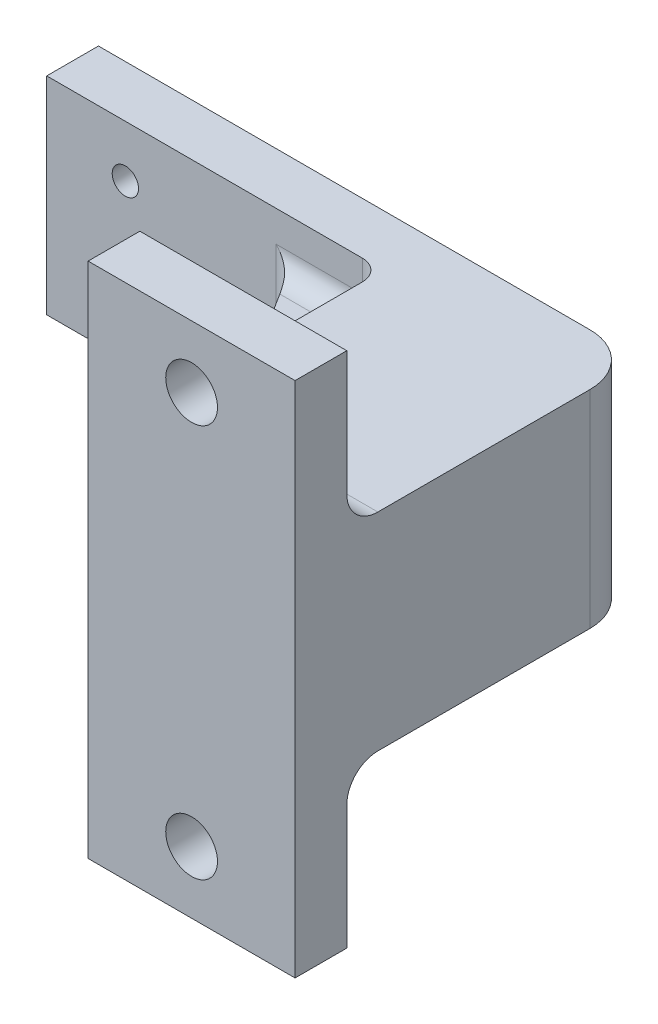
SolidWorks part; units mm, degrees
ref_plane "前视基准面" through (0, 0, 0) normal (0, 0, 1) x (1, 0, 0)
ref_plane "上视基准面" through (0, 0, 0) normal (0, 1, 0) x (1, 0, 0)
ref_plane "右视基准面" through (0, 0, 0) normal (1, 0, 0) x (0, 0, -1)
other "Configuration Table"
sketch "草图1" plane through (0, 0, 0) normal (0, 0, 1) x (1, 0, 0)
  line L1 (0, 0) -> (52.5, 0)
  line L2 (0, 0) -> (0, -20)
  line L3 (0, -20) -> (52.5, -20)
  line L4 (52.5, 0) -> (52.5, -20)
  circle A0 centre (7.6, -5) radius 1.27
  circle A1 centre (7.6, -15) radius 1.25
  point P9 (0, 0)
  dimension "D3" = 2.54
  dimension "D4" = 2.5
  dimension "D1" = 20
  dimension "D2" = 52.5
  dimension "D5" = 10
  dimension "D6" = 5
  dimension "D7" = 7.6
extrude "凸台-拉伸1" add sketch "草图1" along normal blind 5
sketch "草图2" plane through (0, 0, 5) normal (0, 0, 1) x (1, 0, 0)
  line L0 (0, -20) -> (52.5, -20) construction
  line L1 (52.5, 0) -> (32.5, 0)
  line L2 (52.5, 0) -> (52.5, -20)
  line L3 (52.5, -20) -> (32.5, -20)
  line L4 (32.5, 0) -> (32.5, -20)
  dimension "D1" = 20
extrude "凸台-拉伸2" add sketch "草图2" along normal blind 28.5
ref_plane "基准面1" through (0, -10, 0) normal (0, 1, 0) x (1, 0, 0)
sketch "草图4" plane through (0, -10, 0) normal (0, 1, 0) x (1, 0, 0)
  line L0 (32.5, -33.5) -> (32.5, -5) construction
  line L1 (52.5, -33.5) -> (32.5, -33.5)
  line L2 (52.5, -33.5) -> (52.5, -28.5)
  line L3 (52.5, -28.5) -> (32.5, -28.5)
  line L4 (32.5, -33.5) -> (32.5, -28.5)
  dimension "D1" = 5
extrude "凸台-拉伸3" add sketch "草图4" along normal mid plane 50
sketch "草图5" plane through (0, 0, 33.5) normal (0, 0, 1) x (1, 0, 0)
  line L0 (32.5, 15) -> (52.5, 15) construction
  line L1 (32.5, -35) -> (52.5, -35) construction
  circle A0 centre (42.5, 9) radius 2.5
  circle A1 centre (42.5, -29) radius 2.5
  dimension "D1" = 5
  dimension "D2" = 5
  dimension "D3" = 6
  dimension "D4" = 6
extrude "切除-拉伸1" cut sketch "草图5" against normal mid plane 36
fillet "圆角1" radius 3 2 edges at (42.5, 0, 28.5) (42.5, -20, 28.5)
sketch "草图6" plane through (0, -10, 0) normal (0, 1, 0) x (1, 0, 0)
  line L0 (23.2667, -5) -> (32.5, -19.6402)
  line L1 (32.5, -5) -> (0, -5) construction
  line L2 (32.5, -25.5) -> (32.5, -5) construction
rib "筋1" sketch "草图6" sketch "草图6" thickness 10 extrusion direction parallel to sketch draft on no parameters "D1"=10
fillet "圆角2" radius 5 1 edges at (52.5, -10, 0)
fillet "圆角3" radius 2 8 edges at (32.5, -15, 12.3201) (32.5, -5, 12.3201) (32.5, -10, 19.6402) (27.8833, -5, 5) (27.8833, -15, 5) (23.2667, -10, 5) (32.5, -2.5, 5) (32.5, -17.5, 5)
